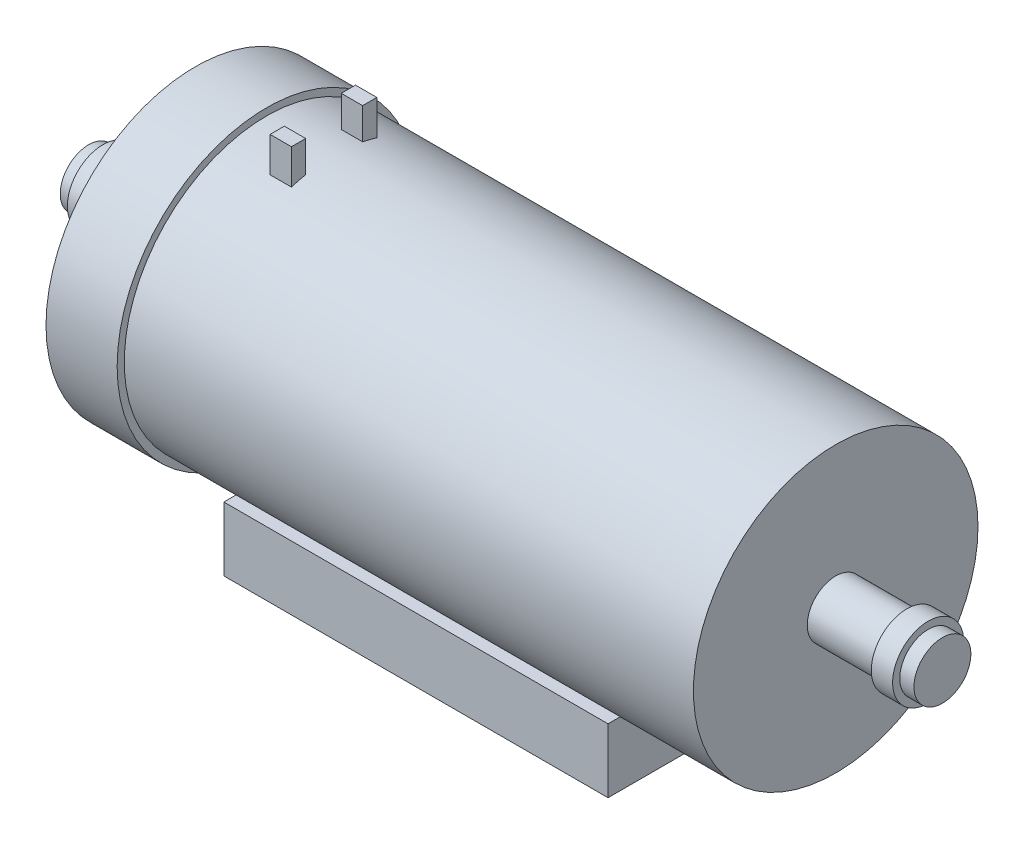
SolidWorks part; units mm, degrees
ref_plane "Front Plane" through (0, 0, 0) normal (0, 0, 1) x (1, 0, 0)
ref_plane "Top Plane" through (0, 0, 0) normal (0, 1, 0) x (1, 0, 0)
ref_plane "Right Plane" through (0, 0, 0) normal (1, 0, 0) x (0, 0, -1)
other "Configuration Table"
sketch "Sketch1" plane through (0, 0, 0) normal (1, 0, 0) x (0, 0, -1)
  circle A0 centre (0, 25) radius 20
  dimension "D1" = 40
extrude "Pump_Body" add sketch "Sketch1" along normal blind 90 from offset 45
sketch "Sketch2" plane through (0, 0, 0) normal (1, 0, 0) x (0, 0, -1)
  circle A0 centre (0, 25) radius 21
extrude "Motor_EndBell" add sketch "Sketch2" along normal blind 10 from offset 45
sketch "Sketch3" plane through (0, 0, 0) normal (0, 1, 0) x (1, 0, 0)
  line L1 (-27, -14) -> (27, -14)
  line L2 (-27, -14) -> (-27, 14)
  line L3 (-27, 14) -> (27, 14)
  line L4 (27, -14) -> (27, 14)
  line L5 (-27, -14) -> (27, 14) construction
  line L6 (-27, 14) -> (27, -14) construction
extrude "Mount_Saddle" add sketch "Sketch3" along normal blind 9
sketch "Sketch4" plane through (0, 0, 0) normal (1, 0, 0) x (0, 0, -1)
  circle A0 centre (0, 25) radius 4
  dimension "D1" = 8
extrude "Inlet_Barb" add sketch "Sketch4" along normal blind 15 from offset 60
sketch "Sketch5" plane through (0, 0, 0) normal (1, 0, 0) x (0, 0, -1)
  circle A0 centre (0, 25) radius 4
  dimension "D1" = 8
extrude "Outlet_Barb" add sketch "Sketch5" along normal blind 15 from offset 45
sketch "Sketch6" plane through (0, 0, 0) normal (1, 0, 0) x (0, 0, -1)
  circle A0 centre (0, 25) radius 5
extrude "Inlet_Ridge" add sketch "Sketch6" along normal blind 3 from offset 58
sketch "Sketch7" plane through (0, 0, 0) normal (1, 0, 0) x (0, 0, -1)
  circle A0 centre (0, 25) radius 5
extrude "Outlet_Ridge" add sketch "Sketch7" along normal blind 3 from offset 55
sketch "Sketch8" plane through (0, 0, 0) normal (0, 1, 0) x (1, 0, 0)
  line L1 (-28.5, 4) -> (-25.5, 4)
  line L2 (-28.5, 4) -> (-28.5, 6)
  line L3 (-28.5, 6) -> (-25.5, 6)
  line L4 (-25.5, 4) -> (-25.5, 6)
  line L5 (-28.5, 4) -> (-25.5, 6) construction
  line L6 (-28.5, 6) -> (-25.5, 4) construction
extrude "Terminal_Pos" add sketch "Sketch8" along normal blind 6 from offset 43
sketch "Sketch9" plane through (0, 0, 0) normal (0, 1, 0) x (1, 0, 0)
  line L1 (-28.5, -6) -> (-25.5, -6)
  line L2 (-28.5, -6) -> (-28.5, -4)
  line L3 (-28.5, -4) -> (-25.5, -4)
  line L4 (-25.5, -6) -> (-25.5, -4)
  line L5 (-28.5, -6) -> (-25.5, -4) construction
  line L6 (-28.5, -4) -> (-25.5, -6) construction
extrude "Terminal_Neg" add sketch "Sketch9" along normal blind 6 from offset 43
equation "\"pump_D\"= 40.0   'ASSUMPTION: Pump body diameter (PDF fallback)"
equation "\"pump_L\"= 90.0   'ASSUMPTION: Pump body length (PDF fallback)"
equation "\"pump_barb_D\"= 8.0   'ASSUMPTION: Pump inlet/outlet barb OD (PDF fallback)"
equation "\"pump_barb_L\"= 15.0   'ASSUMPTION: Barb length (designer choice); inlet/outlet assumed on opposite ends"
equation "\"axis_h\"= 25.0   'ASSUMPTION: Height of the water-line axis above the plate (designer choice)"
equation "\"D1@Sketch1\" = \"pump_D\""
equation "\"D1@Pump_Body\" = \"pump_L\""
equation "\"D1@Sketch4\" = \"pump_barb_D\""
equation "\"D1@Sketch5\" = \"pump_barb_D\""
